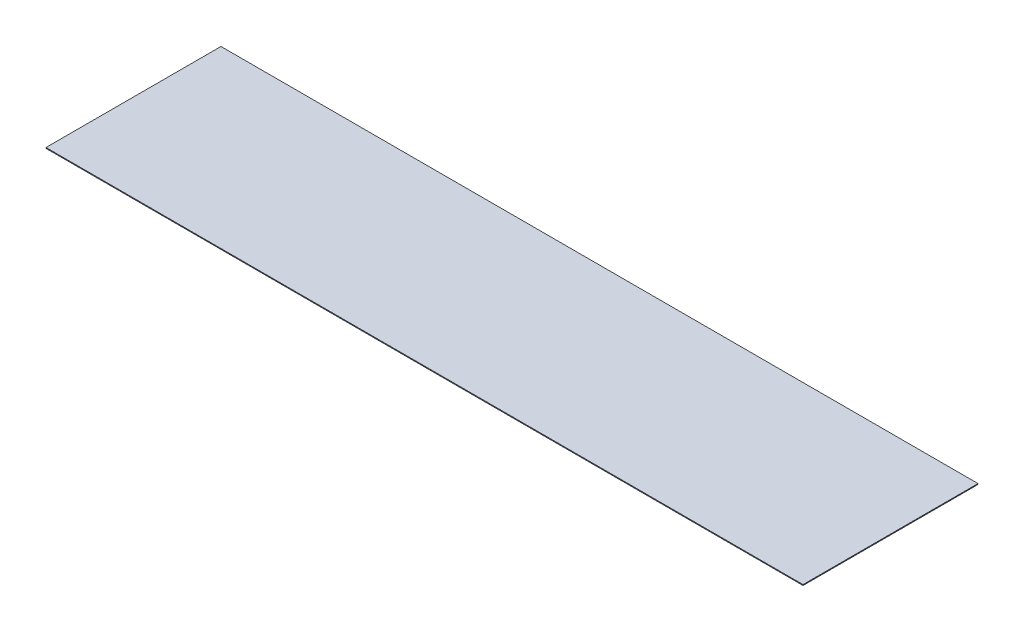
SolidWorks part; units mm, degrees
ref_plane "Alzado" through (0, 0, 0) normal (0, 0, 1) x (1, 0, 0)
ref_plane "Planta" through (0, 0, 0) normal (0, 1, 0) x (1, 0, 0)
ref_plane "Vista lateral" through (0, 0, 0) normal (1, 0, 0) x (0, 0, -1)
sketch "Croquis1" plane through (0, 0, 0) normal (0, 1, 0) x (1, 0, 0)
  line L1 (-900, 208) -> (900, 208)
  line L2 (-900, 208) -> (-900, -208)
  line L3 (-900, -208) -> (900, -208)
  line L4 (900, 208) -> (900, -208)
  line L5 (-900, 208) -> (900, -208) construction
  line L6 (-900, -208) -> (900, 208) construction
  point P0 (0, 0)
extrude "Saliente-Extruir1" add sketch "Croquis1" along normal blind 2
